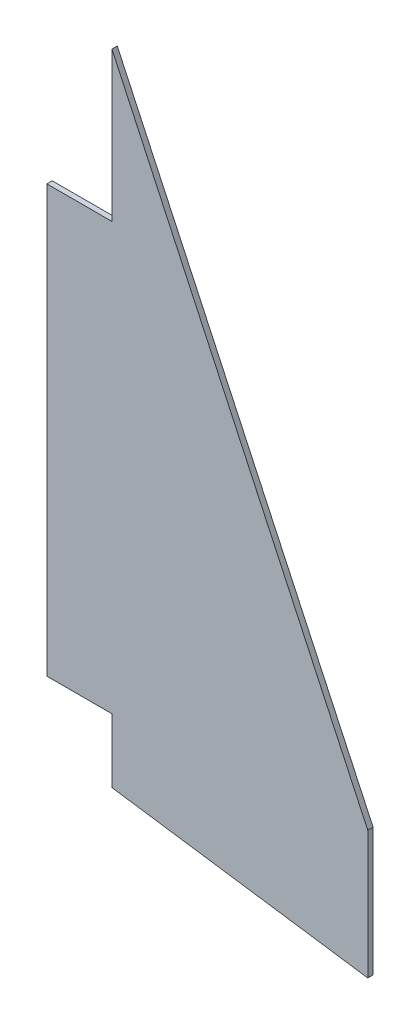
SolidWorks part; units mm, degrees
ref_plane "Front Plane" through (0, 0, 0) normal (0, 0, 1) x (1, 0, 0)
ref_plane "Top Plane" through (0, 0, 0) normal (0, 1, 0) x (1, 0, 0)
ref_plane "Right Plane" through (0, 0, 0) normal (1, 0, 0) x (0, 0, -1)
sketch "Sketch1" plane through (0, 0, 0) normal (0, 0, 1) x (1, 0, 0)
  line L0 (0, 0) -> (0, 381)
  line L1 (0, 381) -> (152.4, 54.1771)
  line L2 (152.4, 54.1771) -> (152.4, -22.0229)
  line L3 (152.4, -22.0229) -> (0, 0)
  line L4 (0, 381) -> (152.4, 381) construction
  point P5 (0, 0)
  point P7 (6, -4.2488)
  dimension "D1" = 65
  dimension "D2" = 381
  dimension "D3" = 152.4
  dimension "D4" = 76.2
extrude "Boss-Extrude1" add sketch "Sketch1" along normal blind 3.175
sketch "Sketch2" plane through (0, 0, 3.175) normal (0, 0, 1) x (1, 0, 0)
  line L0 (0, 381) -> (0, 0) construction
  line L1 (0, 292.1) -> (-38.735, 292.1)
  line L2 (0, 292.1) -> (0, 38.1)
  line L3 (0, 38.1) -> (-38.735, 38.1)
  line L4 (-38.735, 292.1) -> (-38.735, 38.1)
  dimension "D1" = 38.735
  dimension "D2" = 254
  dimension "D3" = 38.1
extrude "Boss-Extrude2" add sketch "Sketch2" against normal up to surface (3.175 mm away) up to face at (76.2, 103.2886, 0)
